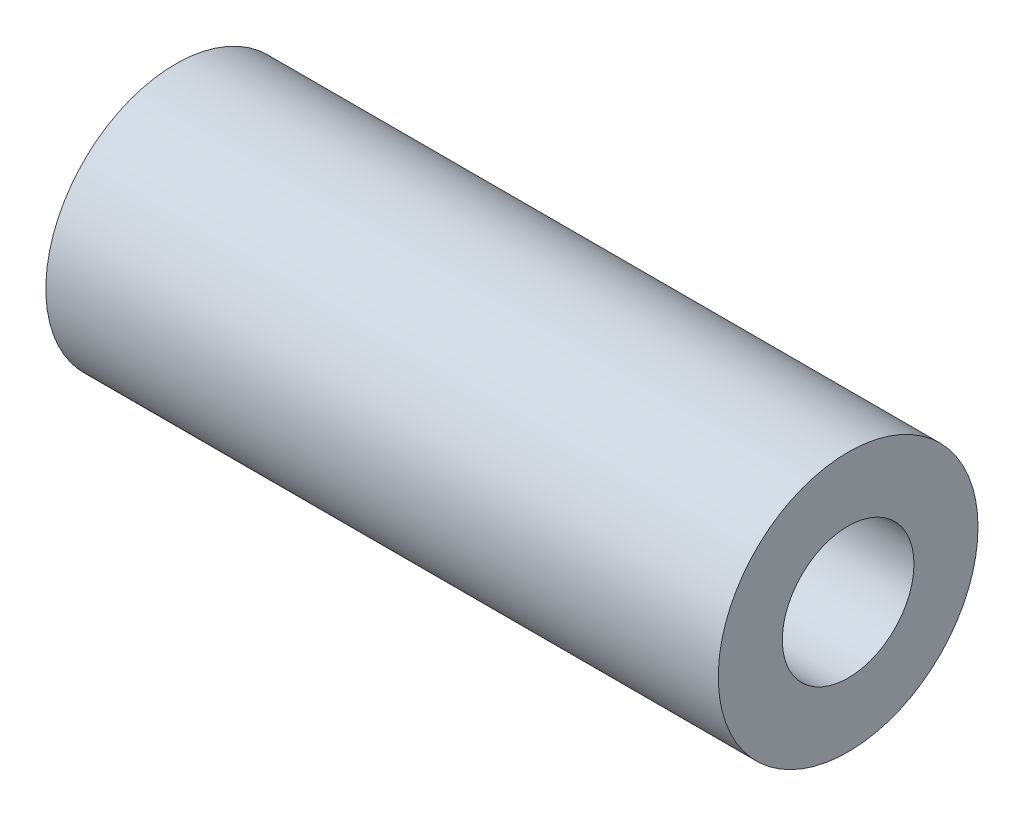
SolidWorks part; units mm, degrees
material "ABS"
ref_plane "Front Plane" through (0, 0, 0) normal (0, 0, 1) x (1, 0, 0)
ref_plane "Top Plane" through (0, 0, 0) normal (0, 1, 0) x (1, 0, 0)
ref_plane "Right Plane" through (0, 0, 0) normal (1, 0, 0) x (0, 0, -1)
sketch "Sketch1" plane through (0, 0, 0) normal (1, 0, 0) x (0, 0, -1)
  circle A0 centre (0, 0) radius 3.2639
  circle A1 centre (0, 0) radius 6.4389
  dimension "D1" = 6.5278
  dimension "D2" = 3.175
extrude "Boss-Extrude1" add sketch "Sketch1" along normal blind 33.3375
